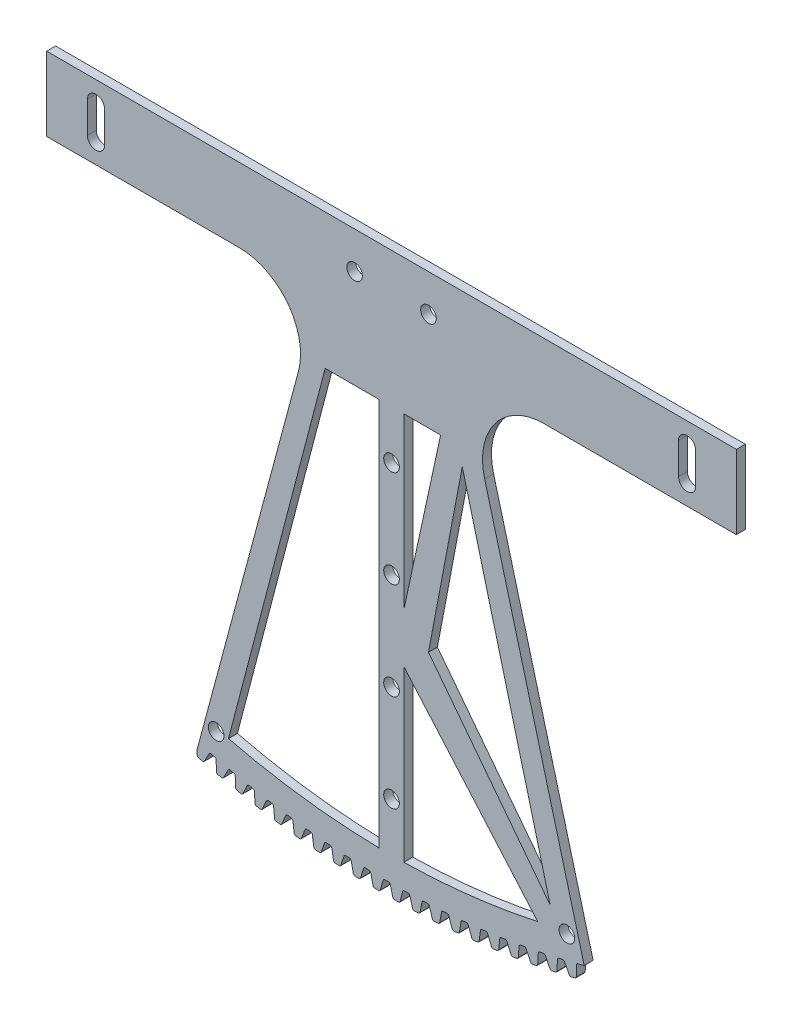
SolidWorks part; units mm, degrees
material "Maple"
ref_plane "Front Plane" through (0, 0, 0) normal (0, 0, 1) x (1, 0, 0)
ref_plane "Top Plane" through (0, 0, 0) normal (0, 1, 0) x (1, 0, 0)
ref_plane "Right Plane" through (0, 0, 0) normal (1, 0, 0) x (0, 0, -1)
sketch "Sketch3" plane through (0, 0, 0) normal (0, 0, 1) x (1, 0, 0)
  line L0 (0, 0) -> (0, -304.8) construction
  line L1 (-21.234, -79.2464) -> (-78.888, -294.4142)
  line L2 (21.234, -79.2464) -> (78.888, -294.4142)
  line L4 (-140, -79.56) -> (140, -79.56)
  line L5 (-140, -79.56) -> (-140, -109.56)
  line L6 (-140, -109.56) -> (140, -109.56)
  line L7 (140, -79.56) -> (140, -109.56)
  line L8 (0, -109.56) -> (0, -79.56) construction
  line L9 (-140, -94.56) -> (140, -94.56) construction
  arc A0 (-78.888, -294.4142) -> (78.888, -294.4142) centre (0, 0) ccw
  point P269 (0, -94.56)
  dimension "D1" = 304.8
  dimension "D4" = 79.56
  dimension "D5" = 30
  dimension "D6" = 280
  dimension "D7" = 140
extrude "Boss-Extrude2" add sketch "Sketch3" along normal blind 3.6286 contours L7 L4 L2 L6 | L1 L6 L2 L4 | L1 L4 L2 | L5 L6 L1 L4 | L1 A0 L2 L6
fillet "Fillet1" radius 25 2 edges at (-29.3565, -109.56, 1.8143) (29.3565, -109.56, 1.8143)
sketch "Sketch4" plane through (0, -79.56, 0) normal (0, 1, 0) x (1, 0, 0)
  line L1 (-140, 0) -> (140, 0)
  line L2 (-140, 0) -> (-140, -3.6286)
  line L3 (-140, -3.6286) -> (140, -3.6286)
  line L4 (140, 0) -> (140, -3.6286)
  line L5 (0, -3.6286) -> (0, 0) construction
  line L6 (-140, -1.8143) -> (140, -1.8143) construction
  point P252 (0, -1.8143)
sketch "Sketch5" plane through (0, 0, 0) normal (0, 0, -1) x (-1, 0, 0)
  line L0 (-123.5, -94.56) -> (-123.5, -100.91)
  line L1 (-116.5, -94.56) -> (-116.5, -100.91)
  line L2 (116.5, -94.56) -> (116.5, -88.21)
  line L3 (140, -79.56) -> (-140, -79.56) construction
  line L4 (-120, -88.21) -> (-120, -100.91) construction
  line L5 (0, -79.56) -> (0, -109.56) construction
  line L6 (-116.5, -94.56) -> (-116.5, -88.21)
  line L7 (-123.5, -94.56) -> (-123.5, -88.21)
  line L8 (116.5, -94.56) -> (116.5, -100.91)
  line L9 (123.5, -94.56) -> (123.5, -100.91)
  line L10 (123.5, -94.56) -> (123.5, -88.21)
  line L11 (-140, -79.56) -> (-140, -109.56) construction
  line L12 (120, -88.21) -> (120, -100.91) construction
  arc A1 (-116.5, -88.21) -> (-123.5, -88.21) centre (-120, -88.21) ccw
  arc A2 (-123.5, -100.91) -> (-116.5, -100.91) centre (-120, -100.91) ccw
  arc A3 (123.5, -100.91) -> (116.5, -100.91) centre (120, -100.91) cw
  arc A4 (116.5, -88.21) -> (123.5, -88.21) centre (120, -88.21) cw
  circle A5 centre (-15, -94.56) radius 3.175
  circle A6 centre (15, -94.56) radius 3.175
  dimension "D1" = 16.5
  dimension "D2" = 7
  dimension "D3" = 8.65
  dimension "D5" = 3.5
  dimension "D6" = 15
  dimension "D8" = 6.35
  dimension "D4" = 6.35
  dimension "D7" = 15
sketch "Sketch13" plane through (0, 0, 0) normal (0, 0, -1) x (-1, 0, 0)
  line L0 (0, 0) -> (78.888, -294.4142)
  line L1 (0, 0) -> (-78.888, -294.4142)
  arc A0 (-78.888, -294.4142) -> (78.888, -294.4142) centre (0, 0) ccw
  arc A1 (-78.888, -294.4142) -> (78.888, -294.4142) centre (0, 0) ccw construction
  arc A2 (-78.888, -294.4142) -> (78.888, -294.4142) centre (0, 0) ccw
  circle A3 centre (0, 0) radius 304.8
  dimension "D1" = 609.6
sketch "Sketch14" plane through (0, 0, 0) normal (0, 0, -1) x (-1, 0, 0)
  line L0 (0, 0) -> (80.0203, -298.6399) construction
  line L2 (78.888, -294.4142) -> (78.9109, -297.0369)
  line L3 (78.9109, -297.0369) -> (76.2891, -297.7211)
  line L18 (76.2891, -297.7211) -> (75.0275, -295.4216)
  line L20 (0, 0) -> (-79.2746, -295.8555) construction
  line L32 (78.888, -294.4142) -> (75.0275, -295.4216)
  line L33 (75.0275, -295.4216) -> (78.888, -294.4142)
  line L34 (0, 0) -> (-75.3952, -296.8678) construction
  line L35 (0, 0) -> (-71.5028, -297.8293) construction
  line L36 (0, 0) -> (-67.5982, -298.7397) construction
  line L37 (0, 0) -> (-63.6821, -299.5989) construction
  line L38 (0, 0) -> (-59.755, -300.4068) construction
  line L39 (0, 0) -> (-55.8176, -301.1633) construction
  line L40 (0, 0) -> (-51.8707, -301.8681) construction
  line L41 (0, 0) -> (-47.9149, -302.5212) construction
  line L42 (0, 0) -> (-43.951, -303.1225) construction
  line L43 (0, 0) -> (-39.9794, -303.6718) construction
  line L44 (0, 0) -> (-36.0011, -304.1691) construction
  line L45 (0, 0) -> (-32.0165, -304.6143) construction
  line L46 (0, 0) -> (-28.0265, -305.0073) construction
  line L47 (0, 0) -> (-24.0316, -305.348) construction
  line L48 (0, 0) -> (-20.0327, -305.6364) construction
  line L49 (0, 0) -> (-16.0303, -305.8724) construction
  line L50 (0, 0) -> (-12.0252, -306.0561) construction
  line L51 (0, 0) -> (-8.018, -306.1873) construction
  line L52 (0, 0) -> (-4.0094, -306.266) construction
  line L53 (0, 0) -> (-0.0002, -306.2922) construction
  line L54 (0, 0) -> (4.0091, -306.266) construction
  line L55 (0, 0) -> (8.0176, -306.1873) construction
  line L56 (0, 0) -> (12.0248, -306.0561) construction
  line L57 (0, 0) -> (16.03, -305.8725) construction
  line L58 (0, 0) -> (20.0323, -305.6364) construction
  line L59 (0, 0) -> (24.0313, -305.348) construction
  line L60 (0, 0) -> (28.0261, -305.0073) construction
  line L61 (0, 0) -> (32.0162, -304.6143) construction
  line L62 (0, 0) -> (36.0007, -304.1691) construction
  line L63 (0, 0) -> (39.9791, -303.6719) construction
  line L64 (0, 0) -> (43.9506, -303.1225) construction
  line L65 (0, 0) -> (47.9146, -302.5213) construction
  line L66 (0, 0) -> (51.8704, -301.8682) construction
  line L67 (0, 0) -> (55.8173, -301.1633) construction
  line L68 (0, 0) -> (59.7546, -300.4069) construction
  line L69 (0, 0) -> (63.6817, -299.599) construction
  line L70 (0, 0) -> (67.5979, -298.7398) construction
  line L71 (0, 0) -> (71.5025, -297.8293) construction
  line L72 (0, 0) -> (75.3948, -296.8679) construction
  line L73 (0, 0) -> (-79.2746, -295.8555) construction
  line L74 (0, 0) -> (-75.3952, -296.8678) construction
  line L137 (37.789, -141.0305) -> (78.888, -294.4142) construction
  line L138 (-140, -79.56) -> (-140, -109.56)
  line L139 (-140, -109.56) -> (-61.9371, -109.56)
  line L140 (-37.789, -141.0305) -> (-78.888, -294.4142)
  line L141 (78.888, -294.4142) -> (37.789, -141.0305)
  line L142 (61.9371, -109.56) -> (140, -109.56)
  line L143 (140, -109.56) -> (140, -79.56)
  line L144 (140, -79.56) -> (-140, -79.56)
  line L145 (-140, -79.56) -> (-140, -109.56)
  line L146 (-140, -109.56) -> (-61.9371, -109.56)
  line L147 (-37.789, -141.0305) -> (-78.888, -294.4142)
  line L149 (61.9371, -109.56) -> (140, -109.56)
  line L150 (140, -109.56) -> (140, -79.56)
  line L151 (140, -79.56) -> (-140, -79.56)
  circle A0 centre (0, 0) radius 307.34
  circle A1 centre (0, 0) radius 302.26
  arc A3 (-37.789, -141.0305) -> (-61.9371, -109.56) centre (-61.9371, -134.56) ccw
  arc A5 (61.9371, -109.56) -> (37.789, -141.0305) centre (61.9371, -134.56) ccw
  arc A6 (-37.789, -141.0305) -> (-61.9371, -109.56) centre (-61.9371, -134.56) ccw
  arc A8 (61.9371, -109.56) -> (37.789, -141.0305) centre (61.9371, -134.56) ccw
  arc A11 (-78.888, -294.4142) -> (78.888, -294.4142) centre (0, 0) ccw
  arc A12 (-78.888, -294.4142) -> (78.888, -294.4142) centre (0, 0) ccw
  dimension "D5" = 614.68
  dimension "D6" = 30
  dimension "D7" = 40
  dimension "D4" = 604.52
  dimension "D1" = 14.5
  dimension "D3" = 14.5
  dimension "D8" = 0.75
  dimension "D9" = 306.2922
  dimension "D10" = 0.75
  dimension "D2" = 0
extrude "Boss-Extrude4" add sketch "Sketch14" against normal up to surface (3.6286 mm away) up to face at (0, -146.6727, 3.6286)
sketch "Sketch15" plane through (0, 0, 0) normal (1, 0, 0) x (0, 0, -1)
  line L0 (0, 0) -> (-23.3364, 0) construction
sketch "Sketch16" plane through (0, 0, 0) normal (0, 0, -1) x (-1, 0, 0)
  line L0 (75.0275, -295.4216) -> (73.7653, -293.1208)
  line L1 (73.7653, -293.1208) -> (71.1999, -293.7544)
  line L2 (71.1999, -293.7544) -> (71.1541, -296.3784)
  line L3 (0, 0) -> (71.5025, -297.8293) construction
  line L4 (0, 0) -> (75.3948, -296.8679) construction
  circle A0 centre (0, 0) radius 302.26 construction
  arc A1 (-78.888, -294.4142) -> (78.888, -294.4142) centre (0, 0) ccw construction
  dimension "D1" = 14.5
  dimension "D2" = 14.5
extrude "Cut-Extrude2" cut sketch "Sketch16" against normal through all and the other way through all
fillet "Fillet2" radius 0.7 2 edges at (-76.2891, -297.7211, 1.8143) (-78.9109, -297.0369, 1.8143)
pattern_circular "CirPattern8" count 20 every 1.5 about axis through (0, 0, 0) along (0, 0, 1) of "Cut-Extrude2", "Boss-Extrude4", "Fillet2"
extrude "Cut-Extrude3" cut sketch "Sketch5" against normal through all
sketch "Sketch17" plane through (0, 0, 0) normal (0, 0, -1) x (-1, 0, 0)
  line L0 (0, -79.56) -> (0, -134.56) construction
  line L1 (140, -79.56) -> (-140, -79.56) construction
  line L2 (-61.9371, -109.56) -> (61.9371, -109.56) construction
  line L3 (-36.9371, -134.56) -> (-26.9371, -134.56) construction
  line L4 (-36.9371, -134.56) -> (-26.9371, -134.56) construction
  line L5 (-26.9371, -134.56) -> (-66.1944, -284.3612) construction
  line L6 (-66.1944, -284.3612) -> (-76.1944, -284.3612) construction
  line L7 (0, -292.2593) -> (5, -292.2593) construction
  line L8 (-37.789, -141.0305) -> (-78.888, -294.4142) construction
  line L9 (0, -134.56) -> (-5, -134.56) construction
  line L10 (0, -134.56) -> (5, -134.56) construction
  line L11 (26.9371, -134.56) -> (36.9371, -134.56) construction
  line L12 (-5, -134.56) -> (-5, -292.2593) construction
  line L13 (36.9371, -134.56) -> (26.9371, -134.56) construction
  line L14 (26.9371, -134.56) -> (66.1944, -284.3612) construction
  line L15 (66.1944, -284.3612) -> (76.1944, -284.3612) construction
  line L16 (37.789, -141.0305) -> (78.888, -294.4142) construction
  line L17 (0.6571, -302.2593) -> (-3.5916, -302.2593) construction
  line L18 (-5, -134.56) -> (5, -134.56) construction
  line L19 (-3.5916, -292.2593) -> (-5, -292.2593) construction
  line L20 (5, -134.56) -> (5, -292.2593) construction
  line L21 (-3.5916, -302.2593) -> (-3.5916, -292.2593) construction
  line L22 (0, -193.6972) -> (0, -233.1221) construction
  line L24 (-66.1944, -284.3612) -> (-68.6354, -294.3612) construction
  line L25 (-67.3487, -294.6613) -> (-69.9221, -294.0612) construction
  line L26 (71.1999, -293.7544) -> (66.067, -294.9513) construction
  line L27 (66.1944, -284.3612) -> (68.6335, -294.3529) construction
  line L28 (26.9371, -134.56) -> (66.1944, -284.3612)
  line L29 (26.9371, -134.56) -> (5, -134.56)
  line L30 (5, -134.56) -> (5, -292.2593)
  line L31 (-66.1944, -284.3612) -> (-26.9371, -134.56)
  line L32 (-26.9371, -134.56) -> (-5, -134.56)
  line L33 (-5, -134.56) -> (-5, -292.2593)
  line L35 (66.1944, -284.3612) -> (57.6779, -286.2946)
  line L36 (66.1944, -284.3612) -> (64.4199, -277.5899) construction
  line L41 (26.9371, -134.56) -> (28.7117, -141.3313) construction
  line L42 (26.9371, -134.56) -> (19.9371, -134.56) construction
  line L44 (28.7117, -141.3313) -> (26.9371, -134.56) construction
  line L48 (-59.3729, -285.9321) -> (-5, -223.4096)
  line L50 (-64.4199, -277.5899) -> (-15, -213.4096)
  line L51 (-15, -213.4096) -> (-28.7117, -141.3313)
  line L52 (-5, -203.4096) -> (-19.9371, -134.56)
  circle A0 centre (0, -272.5469) radius 3.175
  arc A1 (61.9371, -109.56) -> (37.789, -141.0305) centre (61.9371, -134.56) ccw construction
  arc A2 (-37.789, -141.0305) -> (-61.9371, -109.56) centre (-61.9371, -134.56) ccw construction
  arc A3 (-66.1944, -284.3612) -> (-5, -292.2593) centre (0, -12.5018) ccw
  arc A4 (5, -292.2593) -> (66.1944, -284.3612) centre (0, -12.5018) ccw
  circle A5 centre (0, -233.1221) radius 3.175
  circle A6 centre (0, -193.6972) radius 3.175
  circle A7 centre (0, -154.2724) radius 3.175
  circle A8 centre (-71.1944, -284.3612) radius 3.175
  circle A9 centre (71.1944, -284.3612) radius 3.175
  arc A13 (19.9371, -134.56) -> (28.7117, -141.3313) centre (26.9371, -134.56) ccw construction
  arc A14 (19.9371, -134.56) -> (28.7117, -141.3313) centre (26.9371, -134.56) ccw construction
  arc A15 (-59.3729, -285.9321) -> (-64.4199, -277.5899) centre (-66.1944, -284.3612) ccw construction
  arc A16 (-64.4199, -277.5899) -> (-59.3729, -285.9321) centre (-66.1944, -284.3612) cw
  arc A17 (-5, -203.4096) -> (-5, -223.4096) centre (-5, -213.4096) ccw construction
  arc A18 (-28.7117, -141.3313) -> (-19.9371, -134.56) centre (-26.9371, -134.56) ccw construction
  arc A19 (5, -223.4096) -> (5, -203.4096) centre (5, -213.4096) ccw construction
  arc A20 (64.4199, -277.5899) -> (59.3729, -285.9321) centre (66.1944, -284.3612) ccw construction
  dimension "D13" = 6.35
  dimension "D14" = 6.35
  dimension "D15" = 10
  dimension "D16" = 7
  dimension "D17" = 7
  dimension "D20" = 7
  dimension "D21" = 10
  dimension "D22" = 7
  dimension "D18" = 7
  dimension "D1" = 10
  dimension "D2" = 5
  dimension "D3" = 10
  dimension "D4" = 10
  dimension "D5" = 5
  dimension "D6" = 5
  dimension "D7" = 10
  dimension "D8" = 10
  dimension "D9" = 5
  dimension "D10" = 10
  dimension "D11" = 157.6993
  dimension "D12" = 10
  dimension "D19" = 12.241
extrude "Cut-Extrude4" cut sketch "Sketch17" against normal through all
fillet "Fillet3" radius 0.7 39 edges at (-73.7653, -293.1208, 1.8143) (-8.5691, -302.1385, 1.8143) (-11.2101, -302.0521, 1.8143) (-16.4752, -301.8107, 1.8143) (-19.113, -301.6551, 1.8143) (-24.37, -301.276, 1.8143) (-27.0029, -301.0514, 1.8143) (-32.2482, -300.5348, 1.8143) (-34.8743, -300.2414, 1.8143) (-40.1042, -299.5877, 1.8143) (-42.7217, -299.2256, 1.8143) (-47.9327, -298.4352, 1.8143) (-50.5399, -298.0047, 1.8143) (-55.7284, -297.0782, 1.8143) (-58.3234, -296.5796, 1.8143) (-63.4859, -295.5176, 1.8143) (-66.067, -294.9513, 1.8143) (-71.1999, -293.7544, 1.8143) (75.039, -292.7973, 1.8143) (69.9221, -294.0612, 1.8143) (67.3487, -294.6613, 1.8143) (62.2005, -295.7908, 1.8143) (59.6123, -296.3233, 1.8143) (54.4363, -297.3177, 1.8143) (51.835, -297.7822, 1.8143) (46.6348, -298.6408, 1.8143) (44.0223, -299.037, 1.8143) (38.8013, -299.7592, 1.8143) (36.1793, -300.0869, 1.8143) (30.9412, -300.6722, 1.8143) (28.3115, -300.9312, 1.8143) (23.06, -301.3791, 1.8143) (20.4244, -301.5692, 1.8143) (15.1629, -301.8794, 1.8143) (12.5232, -302.0005, 1.8143) (7.2554, -302.1729, 1.8143) (4.6135, -302.2248, 1.8143) (-0.6571, -302.2593, 1.8143) (-3.2994, -302.242, 1.8143)
sketch "Sketch18" plane through (0, 0, 3.6286) normal (0, 0, 1) x (1, 0, 0)
  line L0 (37.789, -141.0305) -> (78.8881, -294.4142) construction
  line L1 (77.5958, -292.1301) -> (78.385, -295.1012)
  line L2 (78.385, -295.1012) -> (79.6633, -294.7617)
  line L3 (79.6633, -294.7617) -> (78.2307, -291.9607)
  arc A0 (77.5958, -292.1301) -> (78.2307, -291.9607) centre (0, 0) ccw
extrude "Cut-Extrude5" cut sketch "Sketch18" against normal blind 13
equation "\"D7@Sketch3\"=\"D6@Sketch3\"/2"
